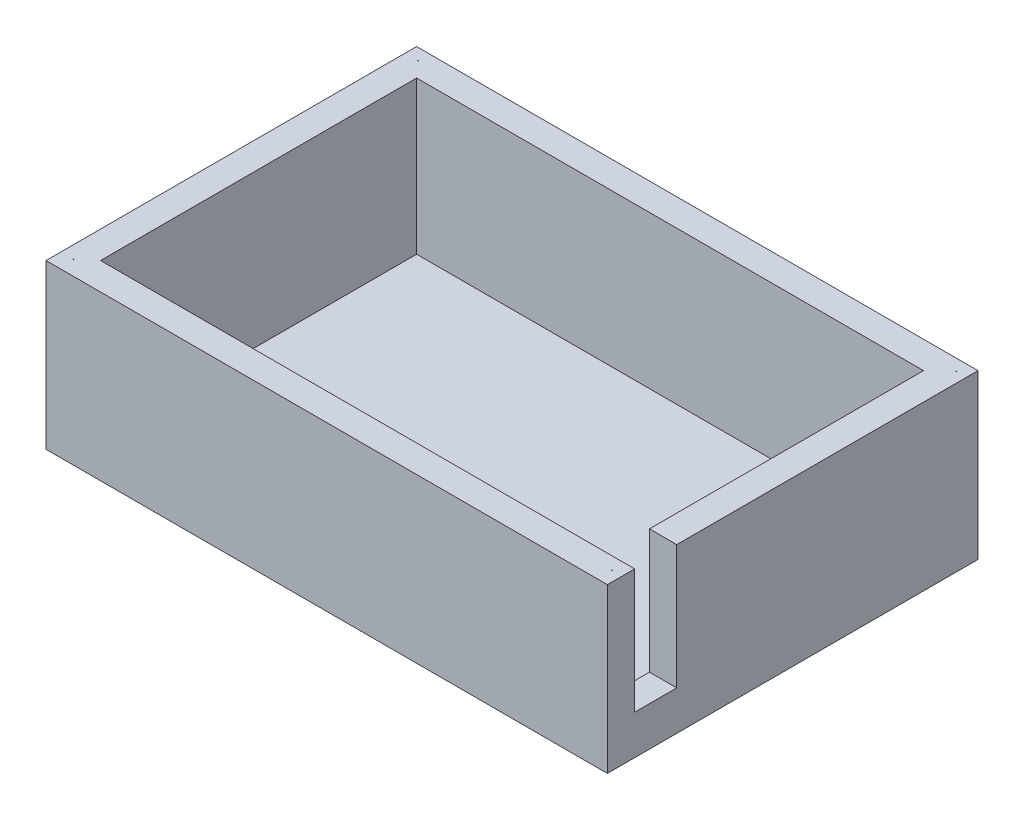
SolidWorks part; units mm, degrees
ref_plane "Front Plane" through (0, 0, 0) normal (0, 0, 1) x (1, 0, 0)
ref_plane "Top Plane" through (0, 0, 0) normal (0, 1, 0) x (1, 0, 0)
ref_plane "Right Plane" through (0, 0, 0) normal (1, 0, 0) x (0, 0, -1)
sketch "Sketch1" plane through (0, 0, 0) normal (0, 1, 0) x (1, 0, 0)
  line L1 (-52, 34.75) -> (51, 34.75)
  line L2 (-52, 34.75) -> (-52, -33.25)
  line L3 (-52, -33.25) -> (51, -33.25)
  line L4 (51, 34.75) -> (51, -33.25)
  line L5 (-52, 34.75) -> (51, -33.25) construction
  line L6 (-52, -33.25) -> (51, 34.75) construction
  point P0 (-0.5, 0.75)
  point P5 (0, 0)
extrude "Boss-Extrude1" add sketch "Sketch1" along normal blind 30
ref_plane "Plane7" through (51, 30, -34.75) normal (0, -1, 0) x (-1, 0, 0)
sketch "Sketch2" plane through (51, 30, -34.75) normal (0, -1, 0) x (1, 0, 0)
  line L1 (-98.0004, 4.9963) -> (-5.0048, 4.9963)
  line L2 (-98.0004, 4.9963) -> (-98.0004, 62.9951)
  line L3 (-98.0004, 62.9951) -> (-5.0048, 62.9951)
  line L4 (-5.0048, 4.9963) -> (-5.0048, 62.9951)
extrude "Cut-Extrude1" cut sketch "Sketch2" along normal blind 28
sketch "Sketch3" plane through (51, 0, 0) normal (1, 0, 0) x (0, 0, -1)
  line L0 (-33.25, 30) -> (34.75, 30) construction
  line L1 (-28.2394, 30) -> (-20.527, 30)
  line L2 (-28.2394, 30) -> (-28.2394, 7.2342)
  line L3 (-28.2394, 7.2342) -> (-20.527, 7.2342)
  line L4 (-20.527, 30) -> (-20.527, 7.2342)
  point P6 (-20.527, 7.2342)
  point P8 (-27.9899, 9.014)
extrude "Cut-Extrude2" cut sketch "Sketch3" against normal blind 28
sketch "Sketch4" plane through (0, 0, -34.75) normal (0, 0, -1) x (-1, 0, 0)
  line L0 (-51, 30) -> (52, 30) construction
  line L1 (-45.9658, 30) -> (46.9236, 30)
  line L2 (-45.9658, 30) -> (-45.9658, 34.5864)
  line L3 (-45.9658, 34.5864) -> (46.9236, 34.5864)
  line L4 (46.9236, 30) -> (46.9236, 34.5864)
hole_wizard "#97 (0.0059) Diameter Hole1" positions "Sketch5" profile "Sketch6" hole size "#97" standard "ANSI Inch" end condition through all
sketch "Sketch5" plane through (0, 30, 0) normal (0, 1, 0) x (1, 0, 0)
  point P0 (49.1303, -30.5503)
  point P2 (49.1303, 32.624)
  point P4 (-49.6513, 32.624)
  point P6 (-49.6513, -30.5503)
sketch "Sketch6" plane through (49.1303, 30, 30.5503) normal (1, 0, 0) x (0, 0, 1)
  line L0 (0, 0) -> (0, 30)
  line L1 (0, 30) -> (0.0749, 30)
  line L2 (0.0749, 30) -> (0.0749, 0)
  line L5 (0.0749, 0) -> (0, 0)
  line L11 (0, -6.35) -> (0, 107.95) construction
  dimension "Thru Hole Dia." = 0.1499
  dimension "Thru Hole Depth" = 30
